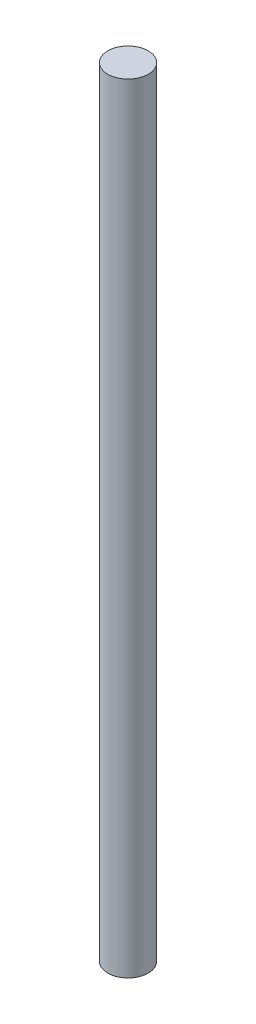
SolidWorks part; units mm, degrees
ref_plane "Front Plane" through (0, 0, 0) normal (0, 0, 1) x (1, 0, 0)
ref_plane "Top Plane" through (0, 0, 0) normal (0, 1, 0) x (1, 0, 0)
ref_plane "Right Plane" through (0, 0, 0) normal (1, 0, 0) x (0, 0, -1)
sketch "Sketch1" plane through (0, 0, 0) normal (0, 1, 0) x (1, 0, 0)
  circle A0 centre (0, 0) radius 15.875
  dimension "D1" = 31.75
extrude "Boss-Extrude1" add sketch "Sketch1" along normal blind 609.6 contours A0
sketch "Sketch2" plane through (0, 0, 0) normal (0, -1, 0) x (1, 0, 0)
  circle A0 centre (0, 0) radius 11.43 construction
  circle A1 centre (0, 11.43) radius 2.1971
  circle A2 centre (11.43, 0) radius 2.1971
  circle A3 centre (0, -11.43) radius 2.1971
  circle A4 centre (-11.43, 0) radius 2.1971
  point P5 (0, 0)
  point P6 (0, 0)
  point P7 (0, -10.16)
  dimension "D1" = 22.86
  dimension "D2" = 4.3942
  dimension "D3" = 4
extrude "Cut-Extrude1" cut sketch "Sketch2" against normal blind 76.2
